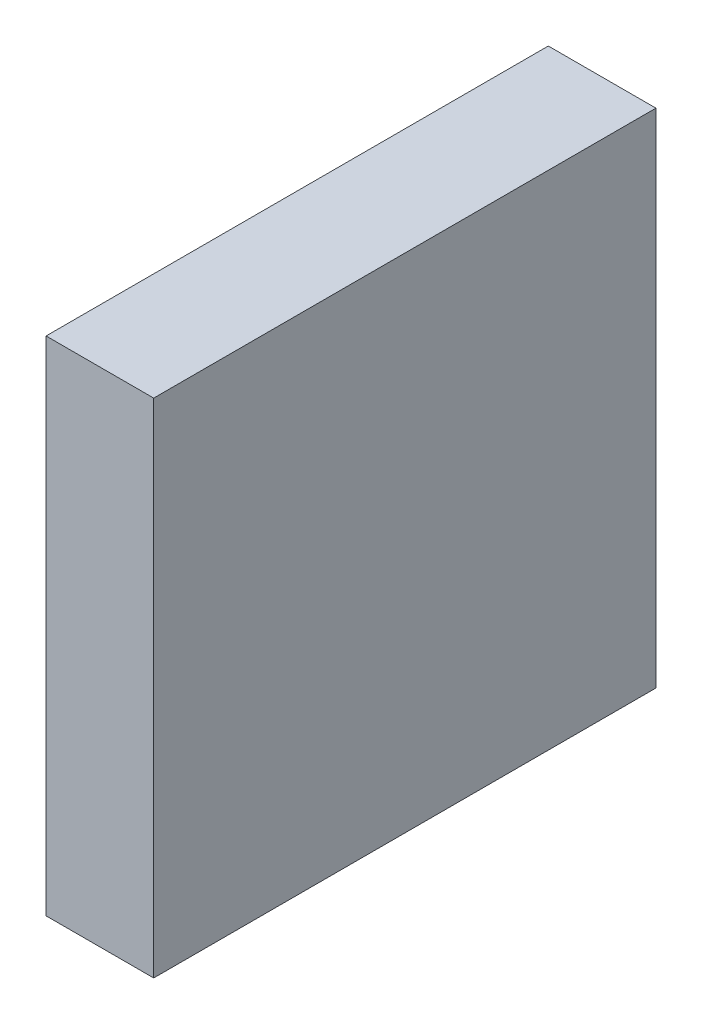
SolidWorks part; units mm, degrees
ref_plane "Front Plane" through (0, 0, 0) normal (0, 0, 1) x (1, 0, 0)
ref_plane "Top Plane" through (0, 0, 0) normal (0, 1, 0) x (1, 0, 0)
ref_plane "Right Plane" through (0, 0, 0) normal (1, 0, 0) x (0, 0, -1)
other "Configuration Table"
sketch "Sketch1" plane through (0, 0, 0) normal (0, 0, 1) x (1, 0, 0)
  line L1 (172.5, 1180) -> (202.5, 1180)
  line L2 (172.5, 1180) -> (172.5, 1320)
  line L3 (172.5, 1320) -> (202.5, 1320)
  line L4 (202.5, 1180) -> (202.5, 1320)
extrude "TOPPING_evap_fan_2_1" add sketch "Sketch1" against normal blind 140 from offset 330 separate body
